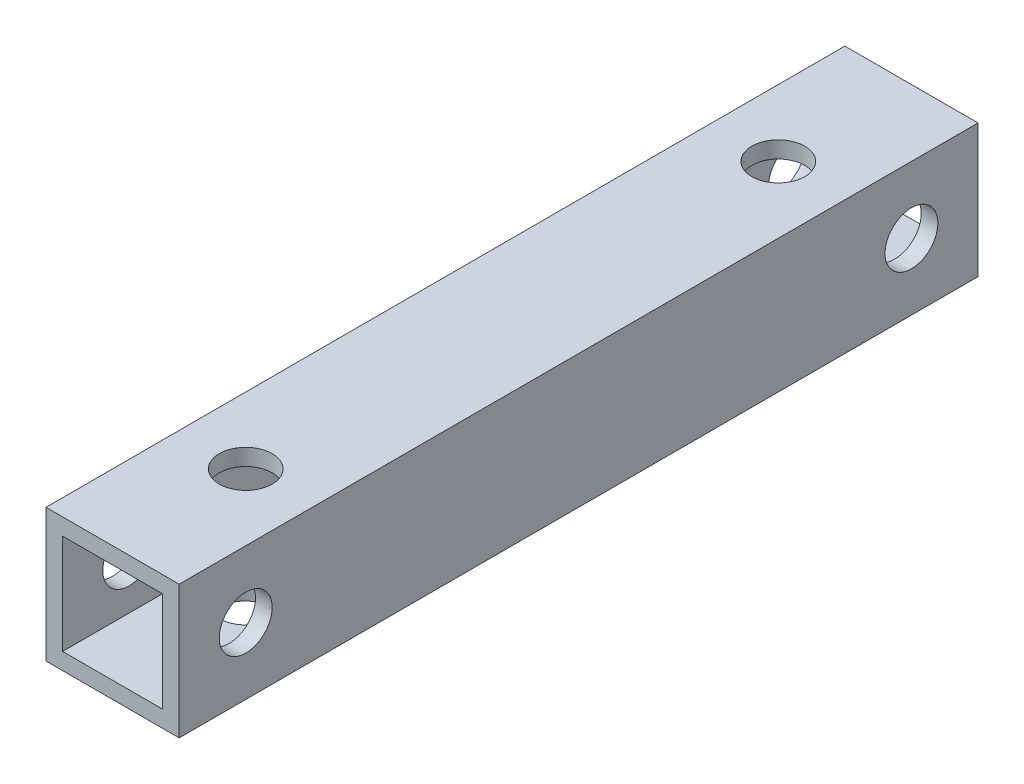
SolidWorks part; units mm, degrees
ref_plane "Front Plane" through (0, 0, 0) normal (0, 0, 1) x (1, 0, 0)
ref_plane "Top Plane" through (0, 0, 0) normal (0, 1, 0) x (1, 0, 0)
ref_plane "Right Plane" through (0, 0, 0) normal (1, 0, 0) x (0, 0, -1)
sketch "Sketch1" plane through (0, 0, 0) normal (0, 0, 1) x (1, 0, 0)
  line L1 (-12.7, 12.7) -> (12.7, 12.7)
  line L2 (-12.7, 12.7) -> (-12.7, -12.7)
  line L3 (-12.7, -12.7) -> (12.7, -12.7)
  line L4 (12.7, 12.7) -> (12.7, -12.7)
  line L5 (-12.7, 12.7) -> (12.7, -12.7) construction
  line L6 (-12.7, -12.7) -> (12.7, 12.7) construction
  point P0 (0, 0)
  dimension "D1" = 25.4
extrude "Extrude1" add sketch "Sketch1" against normal mid plane 152.4
sketch "Sketch2" plane through (0, 0, 76.2) normal (0, 0, 1) x (1, 0, 0)
  line L8 (9.525, -9.525) -> (9.525, 9.525)
  line L9 (9.525, 9.525) -> (-9.525, 9.525)
  line L10 (-9.525, 9.525) -> (-9.525, -9.525)
  line L11 (-9.525, -9.525) -> (9.525, -9.525)
  line L12 (9.525, -9.525) -> (9.525, 9.525)
  line L13 (9.525, 9.525) -> (-9.525, 9.525)
  line L14 (-9.525, 9.525) -> (-9.525, -9.525)
  line L15 (-9.525, -9.525) -> (9.525, -9.525)
  dimension "D1" = 3.175
extrude "Extrude2" cut sketch "Sketch2" against normal through all
hole_wizard "3/8 Clearance Hole1" positions "Sketch4" profile "Sketch3" hole size "3/8" standard "Ansi Inch" end condition through all
sketch "Sketch4" plane through (12.7, 0, 0) normal (1, 0, 0) x (0, 0, -1)
  line L0 (-63.5, 12.7) -> (-63.5, -12.7) construction
  line L1 (76.2, 12.7) -> (-76.2, 12.7) construction
  line L2 (76.2, -12.7) -> (-76.2, -12.7) construction
  line L4 (-76.2, -12.7) -> (-76.2, 12.7) construction
  point P0 (-63.5, 0)
  dimension "D1" = 12.7
sketch "Sketch3" plane through (12.7, 0, 63.5) normal (0, 1, 0) x (0, 0, -1)
  line L0 (0, 0) -> (0, 25.4)
  line L1 (0, 25.4) -> (5.0419, 25.4)
  line L2 (5.0419, 25.4) -> (5.0419, 0)
  line L5 (5.0419, 0) -> (0, 0)
  line L11 (0, -6.35) -> (0, 107.95) construction
  dimension "Thru Hole Dia." = 10.0838
  dimension "Thru Hole Depth" = 25.4
hole_wizard "3/8 Clearance Hole2" positions "Sketch6" profile "Sketch7" hole size "3/8" standard "Ansi Inch" end condition through all
sketch "Sketch6" plane through (0, 12.7, 0) normal (0, 1, 0) x (-1, 0, 0)
  line L0 (12.7, 50.8) -> (-12.7, 50.8) construction
  line L1 (12.7, -76.2) -> (12.7, 76.2) construction
  line L2 (-12.7, -76.2) -> (-12.7, 76.2) construction
  line L4 (-12.7, 76.2) -> (12.7, 76.2) construction
  point P0 (0, 50.8)
  dimension "D1" = 25.4
sketch "Sketch7" plane through (0, 12.7, 50.8) normal (1, 0, 0) x (0, 0, 1)
  line L0 (0, 0) -> (0, 25.4)
  line L1 (0, 25.4) -> (5.0419, 25.4)
  line L2 (5.0419, 25.4) -> (5.0419, 0)
  line L5 (5.0419, 0) -> (0, 0)
  line L11 (0, -6.35) -> (0, 107.95) construction
  dimension "Thru Hole Dia." = 10.0838
  dimension "Thru Hole Depth" = 25.4
ref_plane "Plane1" through (0, 0, 0) normal (0, 0, 1) x (1, 0, 0)
mirror "Mirror1" about plane through (0, 0, 0) normal (0, 0, 1) of "3/8 Clearance Hole2", "3/8 Clearance Hole1"
